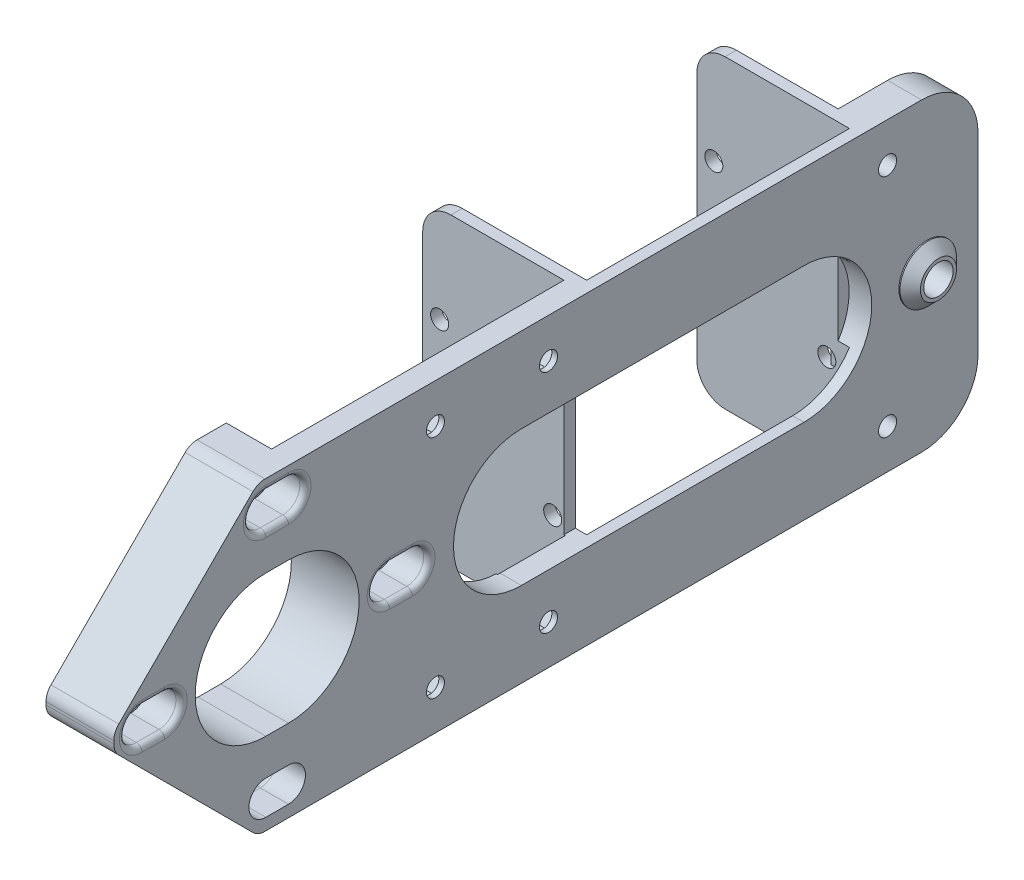
SolidWorks part; units mm, degrees
material "6063-T5"
ref_plane "Front Plane" through (0, 0, 0) normal (1, 0, 0) x (0, 1, 0)
ref_plane "Top Plane" through (0, 0, 0) normal (0, 0, 1) x (0, 1, 0)
ref_plane "Right Plane" through (0, 0, 0) normal (0, 1, 0) x (-1, 0, 0)
sketch "Sketch1" plane through (0, 0, 0) normal (1, 0, 0) x (0, 1, 0)
  line L0 (-27, 0) -> (27, 0) construction
  line L7 (-27, 120) -> (27, 120)
  line L8 (-27, 120) -> (-27, -34)
  line L9 (-27, -34) -> (27, -34)
  line L10 (27, 120) -> (27, -34)
  point P0 (0, 0)
  point P15 (0, 0)
  dimension "D3" = 54
  dimension "D4" = 120
  dimension "D5" = 34
extrude "Boss-Extrude1" add sketch "Sketch1" along normal blind 2
ref_plane "Plane1" through (-46.1, 0, 0) normal (-1, 0, 0) x (0, -1, 0)
sketch "Sketch24" plane through (0, 0, 0) normal (0, 1, 0) x (-1, 0, 0)
  line L0 (0, 10) -> (27, 10) construction
  line L1 (13.5, 33.25) -> (13.5, -13.25) construction
  line L2 (0, -34) -> (0, 120) construction
  line L3 (0, 33.25) -> (27, 33.25)
  line L4 (0, 33.25) -> (0, 35.25)
  line L5 (0, 35.25) -> (27, 35.25)
  line L6 (27, 33.25) -> (27, 35.25)
  line L7 (0, -15.25) -> (27, -15.25)
  line L8 (0, -15.25) -> (0, -13.25)
  line L9 (0, -13.25) -> (27, -13.25)
  line L10 (27, -15.25) -> (27, -13.25)
  line L11 (0, 10) -> (0, 0) construction
  point P5 (13.5, 10)
  point P6 (13.5, 10)
  dimension "D1" = 46.5
  dimension "D2" = 2
  dimension "D3" = 13.5
  dimension "D4" = 10
extrude "Boss-Extrude11" add sketch "Sketch24" along normal up to surface and the other way up to surface up to face at (1, 27, 43) other way up to face at (1, -27, 43)
sketch "Sketch25" plane through (0, 0, 35.25) normal (0, 0, 1) x (1, 0, 0)
  line L0 (-24, 0) -> (-27, 0) construction
  line L1 (-27, -27) -> (-27, 27) construction
  line L2 (-24, -10) -> (-4, -10) construction
  line L3 (-24, -10) -> (-24, 10) construction
  line L4 (-24, 10) -> (-4, 10) construction
  line L5 (-4, -10) -> (-4, 10) construction
  line L6 (-24, -10) -> (-4, 10) construction
  line L7 (-24, 10) -> (-4, -10) construction
  line L8 (-14, 10) -> (-14, 27) construction
  line L9 (-27, 27) -> (0, 27) construction
  circle A0 centre (-24, 10) radius 1.6
  circle A1 centre (-4, 10) radius 1.6
  circle A2 centre (-24, -10) radius 1.6
  circle A3 centre (-4, -10) radius 1.6
  point P1 (-14, 0)
  dimension "D1" = 3.2
  dimension "D2" = 20
  dimension "D3" = 20
  dimension "D4" = 3
extrude "Cut-Extrude13" cut sketch "Sketch25" against normal up to surface (50.5 mm away) up to face at (-13.5, 0, -15.25)
sketch "Sketch11" plane through (0, 0, 0) normal (-1, 0, 0) x (0, -1, 0)
  line L0 (0, 60) -> (0, 0) construction
  line L5 (-27, 96.6714) -> (-27, 87)
  line L8 (-27, 96.6714) -> (-3.6714, 120)
  line L9 (27, 96.6714) -> (3.6714, 120)
  line L10 (-27, 87) -> (0, 60)
  line L11 (0, 60) -> (27, 87)
  line L13 (-27, -34) -> (-27, -15.25) construction
  line L14 (27, 120) -> (27, 35.25) construction
  line L15 (27, 87) -> (27, 96.6714)
  line L16 (-3.6714, 120) -> (3.6714, 120)
  line L17 (-27, 120) -> (27, 120) construction
  point P0 (0, 93)
  dimension "D1" = 60
extrude "Boss-Extrude6" add sketch "Sketch11" along normal blind 10
sketch "Sketch19" plane through (0, 0, 0) normal (-1, 0, 0) x (0, -1, 0)
  line L1 (-27, -34) -> (27, -34)
  line L2 (-27, -34) -> (-27, -14)
  line L3 (-27, -14) -> (27, -14)
  line L4 (27, -34) -> (27, -14)
  dimension "D1" = 14
extrude "Boss-Extrude9" add sketch "Sketch19" along normal blind 4
sketch "Sketch26" plane through (0, 0, 0) normal (-1, 0, 0) x (0, -1, 0)
  line L1 (-27, 120) -> (27, 120)
  line L2 (-27, 120) -> (-27, 35.25)
  line L3 (-27, 35.25) -> (27, 35.25)
  line L4 (27, 120) -> (27, 35.25)
  line L5 (-27, -34) -> (27, -34)
  line L6 (-27, -34) -> (-27, -15.25)
  line L7 (-27, -15.25) -> (27, -15.25)
  line L8 (27, -34) -> (27, -15.25)
extrude "Boss-Extrude12" add sketch "Sketch26" along normal offset from surface (2 mm away) 4 up to face at (2, 0, 43)
sketch "Sketch8" plane through (2, 0, 0) normal (1, 0, 0) x (0, 1, 0)
  line L0 (-20, 22) -> (0, 22) construction
  line L1 (0, 22) -> (0, 0) construction
  line L2 (-20, 62) -> (-20, -18) construction
  line L11 (20, 62) -> (20, -18) construction
  circle A0 centre (-20, 62) radius 1.6
  circle A1 centre (-20, 42) radius 1.6
  circle A2 centre (-20, 22) radius 1.6
  circle A3 centre (-20, 2) radius 1.6
  circle A4 centre (-20, -18) radius 1.6
  circle A5 centre (20, -18) radius 1.6
  circle A6 centre (20, 2) radius 1.6
  circle A7 centre (20, 22) radius 1.6
  circle A8 centre (20, 42) radius 1.6
  circle A9 centre (20, 62) radius 1.6
  point P7 (-20, 22)
  dimension "D2" = 5
  dimension "D5" = 3.2
  dimension "D1" = 20
  dimension "D3" = 20
  dimension "D4" = 22
extrude "Cut-Extrude3" cut sketch "Sketch8" against normal up to surface (12 mm away) contours A8 | A9 | A0 | A1 | A4 | A5 up to face at (-10, 0, 95.3347)
sketch "Sketch16" plane through (-2, 0, 0) normal (-1, 0, 0) x (0, -1, 0)
  line L1 (-17, 60.2679) -> (-17, 63.7321)
  line L2 (-17, 63.7321) -> (-20, 65.4641)
  line L3 (-20, 65.4641) -> (-23, 63.7321)
  line L4 (-23, 63.7321) -> (-23, 60.2679)
  line L5 (-23, 60.2679) -> (-20, 58.5359)
  line L6 (-20, 58.5359) -> (-17, 60.2679)
  line L7 (-17, 40.2679) -> (-17, 43.7321)
  line L8 (-17, 43.7321) -> (-20, 45.4641)
  line L9 (-20, 45.4641) -> (-23, 43.7321)
  line L10 (-23, 43.7321) -> (-23, 40.2679)
  line L11 (-23, 40.2679) -> (-20, 38.5359)
  line L12 (-20, 38.5359) -> (-17, 40.2679)
  line L13 (23, 40.2679) -> (23, 43.7321)
  line L14 (23, 43.7321) -> (20, 45.4641)
  line L15 (20, 45.4641) -> (17, 43.7321)
  line L16 (17, 43.7321) -> (17, 40.2679)
  line L17 (17, 40.2679) -> (20, 38.5359)
  line L18 (20, 38.5359) -> (23, 40.2679)
  line L19 (23, 60.2679) -> (23, 63.7321)
  line L20 (23, 63.7321) -> (20, 65.4641)
  line L21 (20, 65.4641) -> (17, 63.7321)
  line L22 (17, 63.7321) -> (17, 60.2679)
  line L23 (17, 60.2679) -> (20, 58.5359)
  line L24 (20, 58.5359) -> (23, 60.2679)
  circle A0 centre (-20, 62) radius 3 construction
  circle A1 centre (-20, 42) radius 3 construction
  circle A2 centre (20, 42) radius 3 construction
  circle A3 centre (20, 62) radius 3 construction
  dimension "D1" = 6
extrude "Cut-Extrude7" cut sketch "Sketch16" against normal blind 3
sketch "Sketch18" plane through (2, 0, 0) normal (1, 0, 0) x (0, 1, 0)
  line L0 (0, 0) -> (0, -25) construction
  circle A0 centre (0, -25) radius 2.6
  dimension "D1" = 5.2
  dimension "D2" = 25
extrude "Cut-Extrude9" cut sketch "Sketch18" against normal up to surface (6 mm away) up to face at (-4, 0, -17.9583)
sketch "Sketch20" plane through (2, 0, 0) normal (-1, 0, 0) x (0, -1, 0)
  circle A0 centre (0, -25) radius 5
  circle A1 centre (0, -25) radius 2.6
  circle A2 centre (0, -25) radius 2.6 construction
  dimension "D1" = 10
  dimension "D2" = 5.2
extrude "Boss-Extrude10" add sketch "Sketch20" against normal blind 2
chamfer "Chamfer3" distance 1.8 angle 45 1 edges at (4, 0, -20)
sketch "Sketch21" plane through (-4, 0, 0) normal (-1, 0, 0) x (0, -1, 0)
  line L1 (-18.2679, -15) -> (-21.7321, -15)
  line L2 (-21.7321, -15) -> (-23.4641, -18)
  line L3 (-23.4641, -18) -> (-21.7321, -21)
  line L4 (-21.7321, -21) -> (-18.2679, -21)
  line L5 (-18.2679, -21) -> (-16.5359, -18)
  line L6 (-16.5359, -18) -> (-18.2679, -15)
  line L7 (21.7321, -15) -> (18.2679, -15)
  line L8 (18.2679, -15) -> (16.5359, -18)
  line L9 (16.5359, -18) -> (18.2679, -21)
  line L10 (18.2679, -21) -> (21.7321, -21)
  line L11 (21.7321, -21) -> (23.4641, -18)
  line L12 (23.4641, -18) -> (21.7321, -15)
  circle A0 centre (-20, -18) radius 3 construction
  circle A1 centre (20, -18) radius 3 construction
  dimension "D1" = 6
extrude "Cut-Extrude10" cut sketch "Sketch21" against normal blind 2.6
sketch "Sketch22" plane through (-4, 0, 0) normal (-1, 0, 0) x (0, -1, 0)
  line L1 (2.3383, -20.95) -> (-2.3383, -20.95)
  line L2 (-2.3383, -20.95) -> (-4.6765, -25)
  line L3 (-4.6765, -25) -> (-2.3383, -29.05)
  line L4 (-2.3383, -29.05) -> (2.3383, -29.05)
  line L5 (2.3383, -29.05) -> (4.6765, -25)
  line L6 (4.6765, -25) -> (2.3383, -20.95)
  circle A0 centre (0, -25) radius 4.05 construction
  dimension "D1" = 8.1
extrude "Cut-Extrude11" cut sketch "Sketch22" against normal blind 4
sketch "Sketch9" plane through (2, 0, 0) normal (1, 0, 0) x (0, 1, 0)
  line L0 (0, 90) -> (0, 0) construction
  line L1 (-21.9203, 90) -> (0, 68.0797) construction
  line L2 (-21.9203, 90) -> (0, 111.9203) construction
  line L3 (0, 111.9203) -> (21.9203, 90) construction
  line L4 (0, 68.0797) -> (21.9203, 90) construction
  line L5 (-21.9203, 90) -> (21.9203, 90) construction
  line L6 (0, 111.9203) -> (0, 68.0797) construction
  line L7 (-38.7976, 81.608) -> (-1.5, 118.9056)
  line L8 (1.5, 118.9056) -> (38.7976, 81.608)
  line L9 (38.7976, 81.608) -> (38.7976, 127.6518)
  line L10 (38.7976, 127.6518) -> (-38.7976, 127.6518)
  line L11 (-38.7976, 127.6518) -> (-38.7976, 81.608)
  line L12 (-38.7976, 81.608) -> (38.7976, 81.608) construction
  line L13 (-1.5, 118.9056) -> (1.5, 118.9056)
  line L14 (0, 118.9056) -> (0, 111.9203) construction
  line L15 (0, 88) -> (0, 92) construction
  line L16 (-12.5, 88) -> (-12.5, 92)
  line L17 (12.5, 88) -> (12.5, 92)
  line L18 (0, 109.9203) -> (0, 113.9203) construction
  line L19 (-1.48, 109.9203) -> (-1.48, 113.9203)
  line L20 (1.48, 109.9203) -> (1.48, 113.9203)
  line L21 (-21.9203, 88) -> (-21.9203, 92) construction
  line L22 (-23.4003, 88) -> (-23.4003, 92)
  line L23 (-20.4403, 88) -> (-20.4403, 92)
  line L24 (0, 66.0797) -> (0, 70.0797) construction
  line L25 (-1.48, 66.0797) -> (-1.48, 70.0797)
  line L26 (1.48, 66.0797) -> (1.48, 70.0797)
  line L27 (21.9203, 88) -> (21.9203, 92) construction
  line L28 (20.4403, 88) -> (20.4403, 92)
  line L29 (23.4003, 88) -> (23.4003, 92)
  arc A4 (-12.5, 88) -> (12.5, 88) centre (0, 88) ccw
  arc A5 (12.5, 92) -> (-12.5, 92) centre (0, 92) ccw
  arc A6 (-1.48, 109.9203) -> (1.48, 109.9203) centre (0, 109.9203) ccw
  arc A7 (1.48, 113.9203) -> (-1.48, 113.9203) centre (0, 113.9203) ccw
  arc A8 (-23.4003, 88) -> (-20.4403, 88) centre (-21.9203, 88) ccw
  arc A9 (-20.4403, 92) -> (-23.4003, 92) centre (-21.9203, 92) ccw
  arc A10 (-1.48, 66.0797) -> (1.48, 66.0797) centre (0, 66.0797) ccw
  arc A11 (1.48, 70.0797) -> (-1.48, 70.0797) centre (0, 70.0797) ccw
  arc A12 (20.4403, 88) -> (23.4003, 88) centre (21.9203, 88) ccw
  arc A13 (23.4003, 92) -> (20.4403, 92) centre (21.9203, 92) ccw
  point P0 (0, 90)
  point P10 (0, 111.9203)
  point P15 (0, 81.608)
  point P20 (0, 90)
  point P31 (-21.9203, 90)
  point P38 (0, 68.0797)
  point P45 (21.9203, 90)
  point P51 (1.5, 113.9203)
  point P52 (0, 113.9203)
  point P53 (-1.5, 113.9203)
  dimension "D1" = 1.48
  dimension "D4" = 12.5
  dimension "D7" = 4
  dimension "D2" = 31
  dimension "D3" = 90
  dimension "D5" = 6
  dimension "D6" = 3
extrude "Cut-Extrude4" cut sketch "Sketch9" against normal up to surface (12 mm away) up to face at (-10, 0, 95.3347)
sketch "Sketch12" plane through (2, 0, 0) normal (1, 0, 0) x (0, 1, 0)
  line L0 (-21.9203, 88) -> (-21.9203, 92) construction
  line L5 (-21.9203, 88) -> (-21.9203, 92) construction
  line L6 (-24.9203, 88) -> (-24.9203, 92)
  line L7 (-18.9203, 88) -> (-18.9203, 92)
  line L8 (0, 109.9203) -> (0, 113.9203) construction
  line L9 (-3, 109.9203) -> (-3, 113.9203)
  line L10 (3, 109.9203) -> (3, 113.9203)
  line L11 (21.9203, 88) -> (21.9203, 92) construction
  line L12 (18.9203, 88) -> (18.9203, 92)
  line L13 (24.9203, 88) -> (24.9203, 92)
  line L14 (0, 66.0797) -> (0, 70.0797) construction
  line L15 (-3, 66.0797) -> (-3, 70.0797)
  line L16 (3, 66.0797) -> (3, 70.0797)
  arc A8 (-24.9203, 88) -> (-18.9203, 88) centre (-21.9203, 88) ccw
  arc A9 (-18.9203, 92) -> (-24.9203, 92) centre (-21.9203, 92) ccw
  arc A10 (-3, 109.9203) -> (3, 109.9203) centre (0, 109.9203) ccw
  arc A11 (3, 113.9203) -> (-3, 113.9203) centre (0, 113.9203) ccw
  arc A12 (18.9203, 88) -> (24.9203, 88) centre (21.9203, 88) ccw
  arc A13 (24.9203, 92) -> (18.9203, 92) centre (21.9203, 92) ccw
  arc A14 (-3, 66.0797) -> (3, 66.0797) centre (0, 66.0797) ccw
  arc A15 (3, 70.0797) -> (-3, 70.0797) centre (0, 70.0797) ccw
  point P4 (-21.9203, 90)
  point P10 (0, 111.9203)
  point P21 (21.9203, 90)
  point P30 (0, 68.0797)
  dimension "D1" = 3
extrude "Cut-Extrude5" cut sketch "Sketch12" against normal offset from surface (6 mm away) 6 up to face at (-10, 0, 68.0797)
fillet "Fillet6" radius 3 4 edges at (-4, 1.5, 118.9056) (-4, -1.5, 118.9056) (-4, 27, 93.4056) (-4, -27, 93.4056)
fillet "Fillet7" radius 1 16 edges at (2, -3, 68.0797) (2, 0, 73.0797) (2, 3, 68.0797) (2, 18.9203, 90) (2, 21.9203, 95) (2, 24.9203, 90) (2, -3, 111.9203) (2, 0, 116.9203) (2, 3, 111.9203) (-4, -18.9203, 90) (-4, -21.9203, 85) (-4, -24.9203, 90) (2, 0, 63.0797) (2, 21.9203, 85) (2, 0, 106.9203) (-4, -21.9203, 95)
sketch "Sketch23" plane through (2, 0, 0) normal (1, 0, 0) x (0, 1, 0)
  line L0 (0, 46.8032) -> (0, -3.1968) construction
  line L1 (12, 46.8032) -> (12, -3.1968)
  line L2 (-12, 46.8032) -> (-12, -3.1968)
  arc A0 (12, 46.8032) -> (-12, 46.8032) centre (0, 46.8032) ccw
  arc A1 (-12, -3.1968) -> (12, -3.1968) centre (0, -3.1968) ccw
  point P2 (0, 21.8032)
  dimension "D1" = 12
  dimension "D2" = 50
extrude "Cut-Extrude12" cut sketch "Sketch23" against normal up to surface (4 mm away)
sketch "Sketch27" plane through (0, 0, 35.25) normal (0, 0, 1) x (1, 0, 0)
  circle A0 centre (-24, 10) radius 3
  circle A1 centre (-24, -10) radius 3
  circle A2 centre (-4, 10) radius 3
  circle A3 centre (-4, -10) radius 3
  circle A4 centre (-24, -10) radius 1.6 construction
  circle A5 centre (-4, 10) radius 1.6 construction
  circle A6 centre (-4, -10) radius 1.6 construction
  dimension "D1" = 6
extrude "Cut-Extrude14" cut sketch "Sketch27" along normal blind 12
sketch "Sketch28" plane through (0, 0, -15) normal (0, 0, -1) x (1, 0, 0)
  circle A0 centre (-24, 10) radius 3
  circle A1 centre (-4, 10) radius 3
  circle A2 centre (-4, -10) radius 3
  circle A3 centre (-24, -10) radius 3
  circle A4 centre (-24, -10) radius 1.6 construction
  arc A5 (-4, -8.4) -> (-4, -11.6) centre (-4, -10) ccw construction
  arc A6 (-4, 11.6) -> (-4, 8.4) centre (-4, 10) ccw construction
  dimension "D1" = 6
extrude "Cut-Extrude15" cut sketch "Sketch28" along normal up to surface (19 mm away) contours A1 | A2 up to face at (-1, 0, -34)
fillet "Fillet8" radius 5 4 edges at (-27, 27, -14.25) (-27, -27, -14.25) (-27, -27, 34.25) (-27, 27, 34.25)
fillet "Fillet9" radius 10 2 edges at (-1, 27, -34) (-1, -27, -34)
